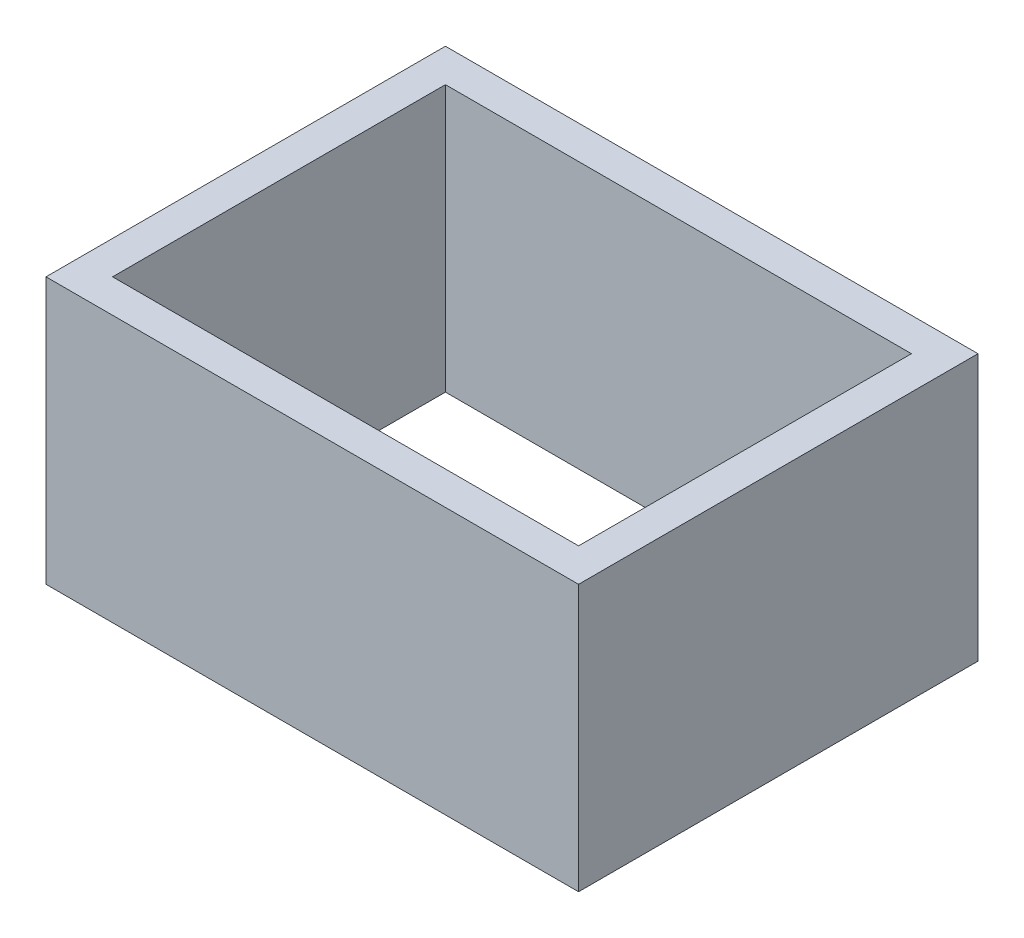
SolidWorks part; units mm, degrees
ref_plane "Front Plane" through (0, 0, 0) normal (0, 0, 1) x (1, 0, 0)
ref_plane "Top Plane" through (0, 0, 0) normal (0, 1, 0) x (1, 0, 0)
ref_plane "Right Plane" through (0, 0, 0) normal (1, 0, 0) x (0, 0, -1)
sketch "Sketch1" plane through (0, 0, 0) normal (0, 1, 0) x (1, 0, 0)
  line L1 (-25.4, 19.05) -> (25.4, 19.05)
  line L2 (-25.4, 19.05) -> (-25.4, -19.05)
  line L3 (-25.4, -19.05) -> (25.4, -19.05)
  line L4 (25.4, 19.05) -> (25.4, -19.05)
  line L5 (-25.4, 19.05) -> (25.4, -19.05) construction
  line L6 (-25.4, -19.05) -> (25.4, 19.05) construction
  point P0 (0, 0)
  dimension "D1" = 38.1
  dimension "D2" = 50.8
extrude "Boss-Extrude1" add sketch "Sketch1" along normal blind 25.4
shell "Shell1" thickness 3.175
